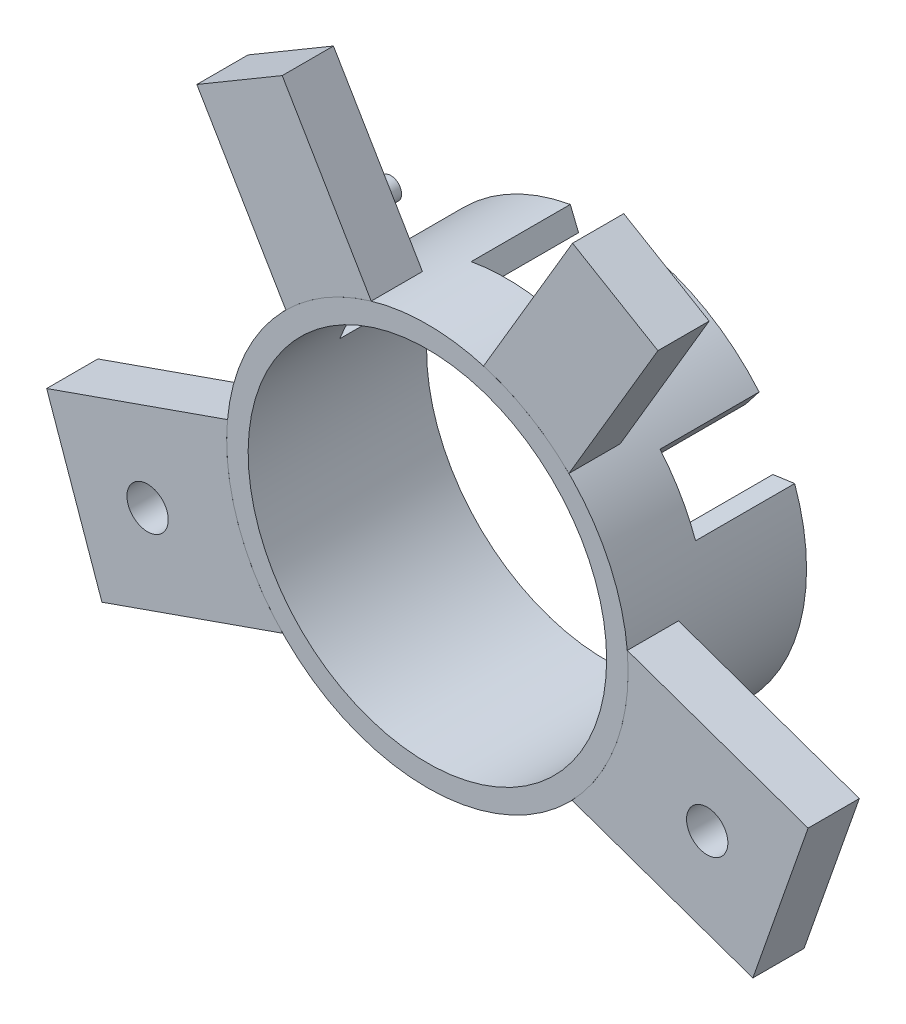
SolidWorks part; units mm, degrees
ref_plane "Ön Düzlem" through (0, 0, 0) normal (0, 0, 1) x (1, 0, 0)
ref_plane "Üst Düzlem" through (0, 0, 0) normal (0, 1, 0) x (1, 0, 0)
ref_plane "Sağ Düzlem" through (0, 0, 0) normal (1, 0, 0) x (0, 0, -1)
sketch "Çizim1" plane through (0, 0, 0) normal (0, 0, 1) x (1, 0, 0)
  circle A0 centre (0, 0) radius 12.15
  circle A1 centre (0, 0) radius 10.85
  dimension "D1" = 24.3
  dimension "D2" = 1.3
extrude "Yükseklik-Ekstrüzyon2" add sketch "Çizim1" along normal blind 10.8
sketch "Çizim2" plane through (0, 0, 0) normal (0, 0, 1) x (1, 0, 0)
  line L0 (1.65, 10.7238) -> (2.15, 11.9583)
  line L1 (-1.65, 10.7238) -> (-2.15, 11.9583)
  line L3 (8.4621, 6.7908) -> (9.2812, 7.8411)
  line L4 (10.1121, 3.933) -> (11.4312, 4.1172)
  line L11 (-10.1121, 3.933) -> (-11.4312, 4.1172)
  line L12 (-8.4621, 6.7908) -> (-9.2812, 7.8411)
  line L13 (-10.1121, -3.933) -> (-11.4312, -4.1172) [skipped]
  line L14 (-8.4621, -6.7908) -> (-9.2812, -7.8411) [skipped]
  line L15 (-1.65, -10.7238) -> (-2.15, -11.9583) [skipped]
  line L16 (1.65, -10.7238) -> (2.15, -11.9583) [skipped]
  line L17 (8.4621, -6.7908) -> (9.2812, -7.8411) [skipped]
  line L18 (10.1121, -3.933) -> (11.4312, -4.1172) [skipped]
  circle A0 centre (0, 0) radius 10.85 construction
  circle A1 centre (0, 0) radius 12.15 construction
  arc A2 (2.15, 11.9583) -> (-2.15, 11.9583) centre (0, 0) ccw
  arc A3 (1.65, 10.7238) -> (-1.65, 10.7238) centre (0, 0) ccw
  arc A4 (11.4312, 4.1172) -> (9.2812, 7.8411) centre (0, 0) ccw
  arc A5 (10.1121, 3.933) -> (8.4621, 6.7908) centre (0, 0) ccw
  arc A12 (-9.2812, 7.8411) -> (-11.4312, 4.1172) centre (0, 0) ccw
  arc A13 (-8.4621, 6.7908) -> (-10.1121, 3.933) centre (0, 0) ccw
  arc A14 (-10.1121, -3.933) -> (-8.4621, -6.7908) centre (0, 0) ccw [skipped]
  arc A15 (-11.4312, -4.1172) -> (-9.2812, -7.8411) centre (0, 0) ccw [skipped]
  arc A16 (-1.65, -10.7238) -> (1.65, -10.7238) centre (0, 0) ccw [skipped]
  arc A17 (-2.15, -11.9583) -> (2.15, -11.9583) centre (0, 0) ccw [skipped]
  arc A18 (9.2812, -7.8411) -> (11.4312, -4.1172) centre (0, 0) ccw [skipped]
  arc A19 (8.4621, -6.7908) -> (10.1121, -3.933) centre (0, 0) ccw [skipped]
  point P8 (0, 10.85)
  point P9 (0, 12.15)
  point P34 (0, 0)
  dimension "D2" = 4.3
  dimension "D1" = 3.3
  dimension "D4" = 6
extrude "Kes-Ekstrüzyon1" cut sketch "Çizim2" along normal blind 6
sketch "Çizim3" plane through (0, 0, 10.8) normal (0, 0, 1) x (1, 0, 0)
  line L0 (3.4, 11.6646) -> (8.7871, 20.7936)
  line L1 (8.7871, 20.7936) -> (13.9545, 17.7443)
  line L2 (13.9545, 17.7443) -> (8.5674, 8.6153)
  line L3 (-8.5674, 8.6153) -> (-13.9545, 17.7443)
  line L4 (-13.9545, 17.7443) -> (-8.7871, 20.7936)
  line L5 (-8.7871, 20.7936) -> (-3.4, 11.6646)
  line L6 (8.7542, -8.4254) -> (19.6993, -12.2678)
  line L7 (19.6993, -12.2678) -> (23.0448, -2.738)
  line L8 (23.0448, -2.738) -> (12.0997, 1.1044)
  line L9 (-12.0997, 1.1044) -> (-23.0448, -2.738)
  line L10 (-23.0448, -2.738) -> (-19.6993, -12.2678)
  line L11 (-19.6993, -12.2678) -> (-8.7542, -8.4254)
  circle A0 centre (0, 0) radius 12.15 construction
  arc A4 (2.15, 11.9583) -> (-2.15, 11.9583) centre (0, 0) ccw construction
  arc A5 (8.7542, -8.4254) -> (12.0997, 1.1044) centre (0, 0) ccw
  arc A6 (-12.0997, 1.1044) -> (-8.7542, -8.4254) centre (0, 0) ccw
  arc A7 (8.5674, 8.6153) -> (3.4, 11.6646) centre (0, 0) ccw
  arc A8 (-3.4, 11.6646) -> (-8.5674, 8.6153) centre (0, 0) ccw
  point P28 (0, 12.15)
  dimension "D1" = 6
  dimension "D2" = 6.8
  dimension "D3" = 3.4
  dimension "D4" = 6
  dimension "D5" = 10.6
  dimension "D6" = 10.6
  dimension "D7" = 6
  dimension "D8" = 6
  dimension "D9" = 11.6
  dimension "D10" = 11.6
  dimension "D11" = 10.1
  dimension "D12" = 8.3
  dimension "D13" = 10.1
  dimension "D14" = 11.6
  dimension "D15" = 11.6
  dimension "D16" = 10.1
  dimension "D17" = 10.1
  dimension "D18" = 8.3
extrude "Yükseklik-Ekstrüzyon3" add sketch "Çizim3" against normal blind 3.1 separate body
sketch "Çizim4" plane through (0, 0, 7.7) normal (0, 0, -1) x (-1, 0, 0)
  line L0 (23.0448, -2.738) -> (19.6993, -12.2678) construction
  line L1 (-19.6993, -12.2678) -> (-23.0448, -2.738) construction
  line L2 (12.0997, 1.1044) -> (23.0448, -2.738) construction
  line L3 (-23.0448, -2.738) -> (-12.0997, 1.1044) construction
  line L5 (13.9545, 17.7443) -> (8.5674, 8.6153) construction
  line L6 (-8.7871, 20.7936) -> (-3.4, 11.6646) construction
  circle A0 centre (7.5725, 12.8323) radius 0.65
  circle A1 centre (-7.5725, 12.8323) radius 0.65
  circle A2 centre (16.9374, -5.946) radius 2.1
  circle A3 centre (-16.9374, -5.946) radius 2.1
  arc A4 (8.5674, 8.6153) -> (3.4, 11.6646) centre (0, 0) ccw construction
  arc A5 (-3.4, 11.6646) -> (-8.5674, 8.6153) centre (0, 0) ccw construction
  point P12 (0, 0)
  dimension "D1" = 1.3
  dimension "D2" = 1.3
  dimension "D3" = 4.2
  dimension "D4" = 4.2
  dimension "D6" = 4.7
  dimension "D11" = 2.1
  dimension "D12" = 2.1
  dimension "D5" = 4.7
  dimension "D7" = 5.05
  dimension "D8" = 5.05
  dimension "D9" = 3
  dimension "D10" = 3
extrude "Yükseklik-Ekstrüzyon4" add sketch "Çizim4" along normal blind 2.26
sketch "Çizim5" plane through (0, 0, 5.44) normal (0, 0, -1) x (-1, 0, 0)
  circle A0 centre (16.9374, -5.946) radius 1.25
  circle A1 centre (-16.9374, -5.946) radius 1.25
  dimension "D1" = 2.5
  dimension "D2" = 2.5
extrude "Kes-Ekstrüzyon2" cut sketch "Çizim5" against normal up to surface (5.36 mm away) up to face at (8.725, 14.7854, 10.8)
